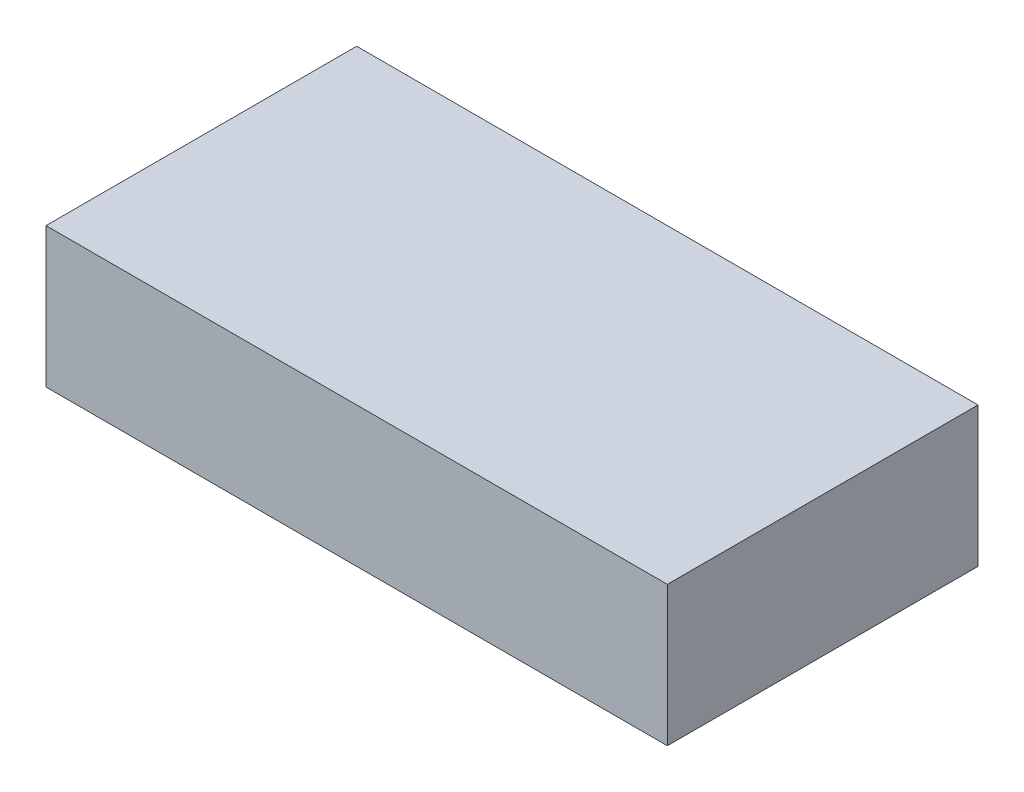
SolidWorks part; units mm, degrees
ref_plane "Plan de face" through (0, 0, 0) normal (0, 0, 1) x (1, 0, 0)
ref_plane "Plan de dessus" through (0, 0, 0) normal (0, 1, 0) x (1, 0, 0)
ref_plane "Plan de droite" through (0, 0, 0) normal (1, 0, 0) x (0, 0, -1)
sketch "Esquisse1" plane through (0, 0, 0) normal (0, 1, 0) x (1, 0, 0)
  line L1 (100, -50) -> (-100, -50)
  line L2 (100, -50) -> (100, 50)
  line L3 (100, 50) -> (-100, 50)
  line L4 (-100, -50) -> (-100, 50)
  line L5 (100, -50) -> (-100, 50) construction
  line L6 (100, 50) -> (-100, -50) construction
  point P0 (0, 0)
  dimension "D1" = 200
  dimension "D2" = 100
extrude "Boss.-Extru.1" add sketch "Esquisse1" along normal blind 45
